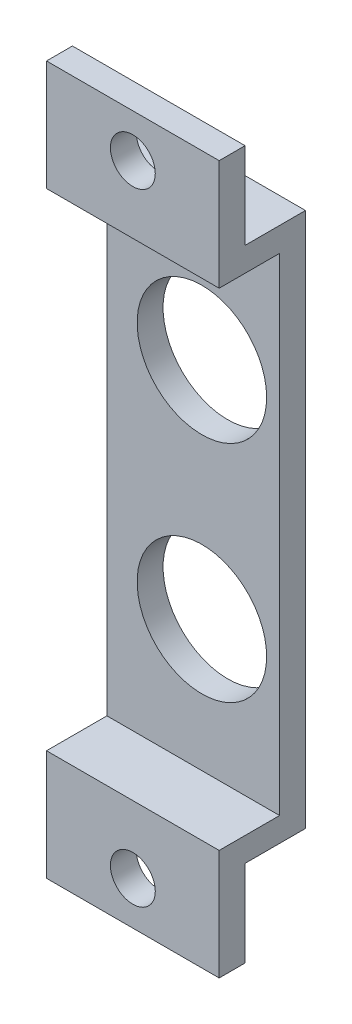
SolidWorks part; units mm, degrees
material "PET"
ref_plane "Front Plane" through (0, 0, 0) normal (0, 0, 1) x (1, 0, 0)
ref_plane "Top Plane" through (0, 0, 0) normal (0, 1, 0) x (1, 0, 0)
ref_plane "Right Plane" through (0, 0, 0) normal (1, 0, 0) x (0, 0, -1)
sketch "Sketch1" plane through (0, 0, 0) normal (0, 0, 1) x (1, 0, 0)
  line L0 (10, 31) -> (-10, -31) construction
  line L1 (10, 31) -> (-10, 31)
  line L2 (10, 31) -> (10, 19.3246)
  line L3 (10, -31) -> (-10, -31)
  line L4 (-10, 31) -> (-10, 15.9394)
  line L5 (10, -31) -> (-10, -41) construction
  line L6 (10, -31) -> (-10, -31)
  line L7 (10, -31) -> (10, -41)
  line L8 (10, -41) -> (-10, -41)
  line L9 (-10, -31) -> (-10, -41)
  line L10 (-10, 31) -> (10, 31)
  line L11 (-10, 31) -> (-10, 41)
  line L12 (-10, 41) -> (10, 41)
  line L13 (10, 31) -> (10, 41)
  line L14 (10, 41) -> (-10, 31) construction
  line L15 (-10, 31) -> (-10.0339, 21.9932) construction
  line L16 (10, 6.6754) -> (10, -6.6754)
  line L17 (10, -19.3246) -> (10, -31)
  line L18 (-9.6, 15.9394) -> (-10, 15.9394)
  line L19 (-9.6, 10.0606) -> (-10, 10.0606)
  line L20 (-10, 10.0606) -> (-10, -10.0606)
  line L21 (-9.6, -10.0606) -> (-10, -10.0606)
  line L22 (-9.6, -15.9394) -> (-10, -15.9394)
  line L23 (-10, -15.9394) -> (-10, -31)
  circle A0 centre (0, -36) radius 2.6
  circle A1 centre (0, 36) radius 2.6
  arc A2 (10, 19.3246) -> (-9.6, 15.9394) centre (1, 13) ccw
  arc A3 (10, -6.6754) -> (-9.6, -10.0606) centre (1, -13) ccw
  arc A4 (-9.6, 10.0606) -> (10, 6.6754) centre (1, 13) ccw
  arc A5 (-9.6, -15.9394) -> (10, -19.3246) centre (1, -13) ccw
  point P4 (0, 0)
  point P15 (0, -36)
  point P17 (0, 36)
  dimension "D2" = 5.2
  dimension "D3" = 5.2
  dimension "D6" = 22
  dimension "D7" = 22
  dimension "D9" = 18
  dimension "D1" = 20
  dimension "D4" = 10
  dimension "D5" = 10
  dimension "D8" = 18
  dimension "D10" = 26
  dimension "D11" = 0.4
  dimension "D12" = 0.4
  dimension "D13" = 0.4
  dimension "D14" = 0.4
extrude "Boss-Extrude1" add sketch "Sketch1" against normal blind 3 contours L1 L13 L12 L11 A1 | L3 L9 L8 L7 A0
ref_plane "Plane1" through (0, 0, -7) normal (0, 0, 1) x (1, 0, 0)
sketch "Sketch4" plane through (0, 0, -7) normal (0, 0, 1) x (1, 0, 0)
  line L0 (10, 31) -> (-10, 31) construction
  line L1 (-10, 31) -> (10, 31)
  line L2 (-10, 31) -> (-10, -31)
  line L3 (-10, -31) -> (10, -31)
  line L4 (10, 31) -> (10, -31)
  line L5 (10, -31) -> (-10, -31) construction
  line L6 (-10, -31) -> (-10, -41) construction
  line L7 (10, -31) -> (10, -41) construction
  line L8 (0, -31) -> (0, 31) construction
  circle A0 centre (1, 13) radius 7.5
  circle A1 centre (1, -13) radius 7.5
  dimension "D1" = 15
  dimension "D2" = 15
  dimension "D3" = 26
  dimension "D4" = 18
  dimension "D5" = 18
  dimension "D6" = 1
  dimension "D7" = 1
extrude "Boss-Extrude2" add sketch "Sketch4" against normal blind 3 separate body
sketch "Sketch5" plane through (0, 0, -7) normal (0, 0, 1) x (1, 0, 0)
  line L0 (10, -31) -> (10, 31) construction
  line L1 (-10, 31) -> (10, 31)
  line L2 (-10, 31) -> (-10, 28.2)
  line L3 (-10, 28.2) -> (10, 28.2)
  line L4 (10, 31) -> (10, 28.2)
  line L5 (-10, 31) -> (-10, -31) construction
  line L6 (10, -31) -> (-10, -31)
  line L7 (10, -31) -> (10, -28.2)
  line L8 (10, -28.2) -> (-10, -28.2)
  line L9 (-10, -31) -> (-10, -28.2)
  dimension "D1" = 2.8
  dimension "D2" = 2.8
extrude "Boss-Extrude3" add sketch "Sketch5" along normal blind 7
